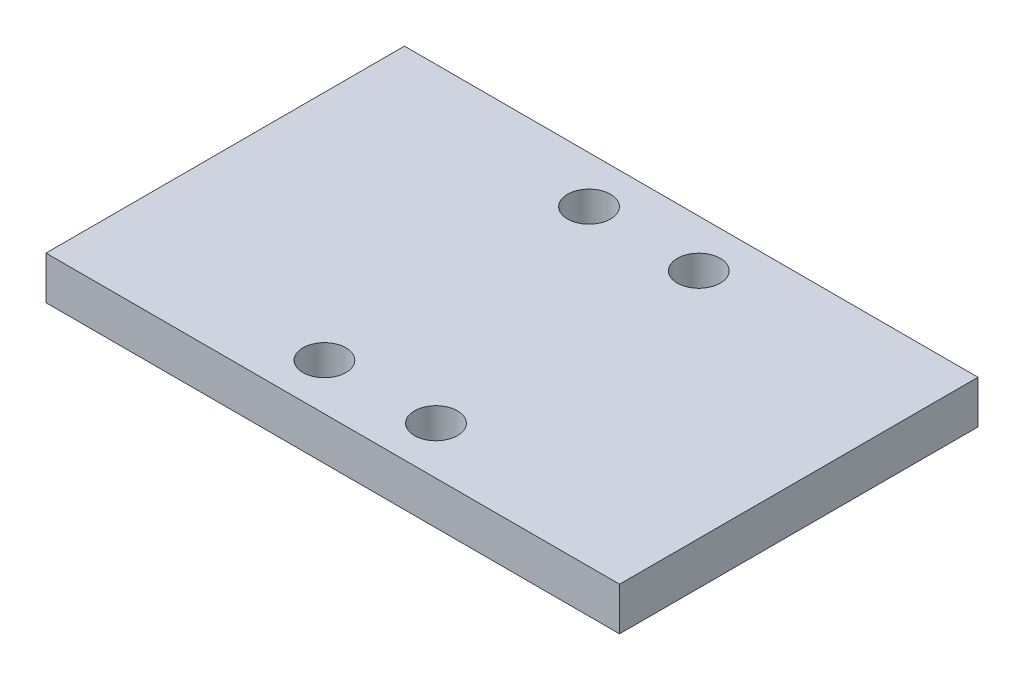
SolidWorks part; units mm, degrees
ref_plane "Front Plane" through (0, 0, 0) normal (0, 0, 1) x (1, 0, 0)
ref_plane "Top Plane" through (0, 0, 0) normal (0, 1, 0) x (1, 0, 0)
ref_plane "Right Plane" through (0, 0, 0) normal (1, 0, 0) x (0, 0, -1)
sketch "Sketch1" plane through (0, 0, 0) normal (0, 1, 0) x (1, 0, 0)
  line L1 (-20, -12.5) -> (20, -12.5)
  line L2 (-20, -12.5) -> (-20, 12.5)
  line L3 (-20, 12.5) -> (20, 12.5)
  line L4 (20, -12.5) -> (20, 12.5)
  line L5 (-20, -12.5) -> (20, 12.5) construction
  line L6 (-20, 12.5) -> (20, -12.5) construction
  point P0 (0, 0)
extrude "Boss-Extrude1" add sketch "Sketch1" along normal blind 3
sketch "Sketch2" plane through (0, 0, 0) normal (0, -1, 0) x (1, 0, 0)
  circle A0 centre (-3.8685, -9.2406) radius 1.5
  circle A1 centre (3.8313, -9.1969) radius 1.5
  circle A2 centre (3.8767, 9.1779) radius 1.5
  circle A3 centre (-3.8228, 9.2596) radius 1.5
extrude "Cut-Extrude1" cut sketch "Sketch2" against normal through all
